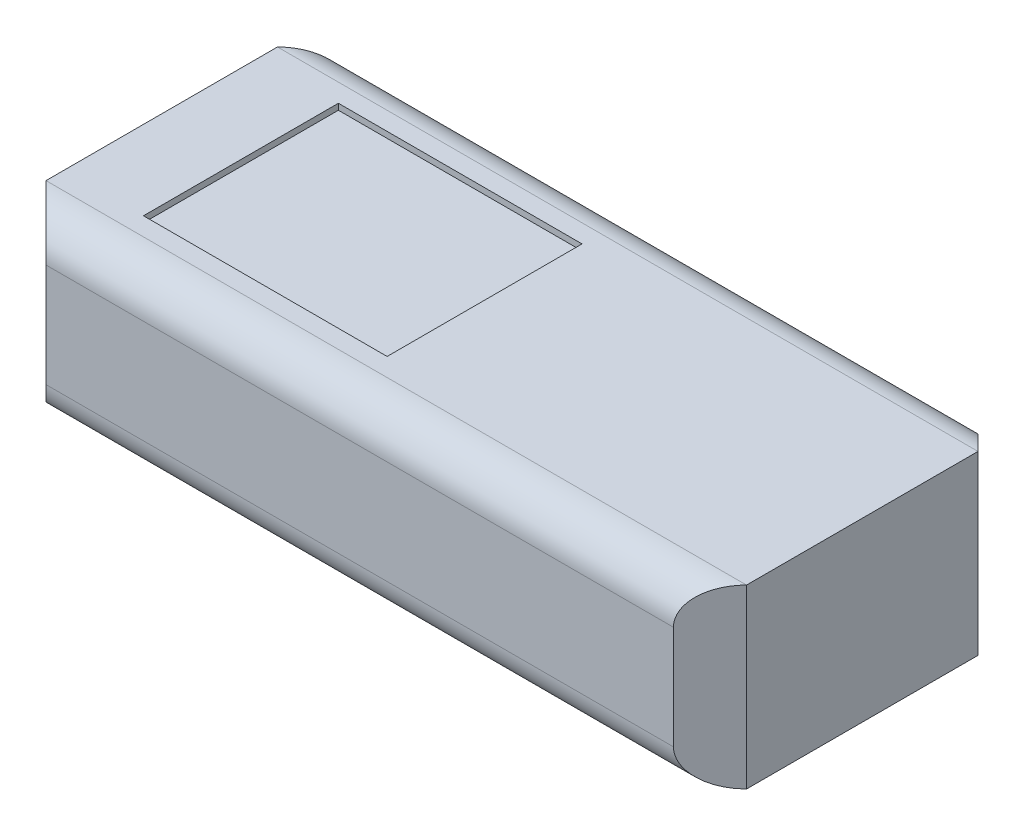
SolidWorks part; units mm, degrees
ref_plane "Front Plane" through (0, 0, 0) normal (0, 0, 1) x (1, 0, 0)
ref_plane "Top Plane" through (0, 0, 0) normal (0, 1, 0) x (1, 0, 0)
ref_plane "Right Plane" through (0, 0, 0) normal (1, 0, 0) x (0, 0, -1)
sketch "Sketch1" plane through (0, 0, 0) normal (0, 1, 0) x (1, 0, 0)
  line L0 (0, -55) -> (0, 55) construction
  line L1 (-57.5, 25) -> (57.5, 25)
  line L2 (-57.5, 25) -> (-57.5, -25)
  line L3 (-57.5, -25) -> (57.5, -25)
  line L4 (57.5, 25) -> (57.5, -25)
  line L5 (-55, 0) -> (55, 0) construction
  dimension "D1" = 50
  dimension "D2" = 115
  dimension "D3" = 57.5
  dimension "D4" = 25
extrude "Boss-Extrude1" add sketch "Sketch1" along normal blind 29
chamfer "Chamfer1" distance 6 angle 45 4 edges at (57.5, 14.5, -25) (57.5, 14.5, 25) (-57.5, 14.5, -25) (-57.5, 14.5, 25)
fillet "Fillet1" radius 6 4 edges at (0, 0, 25) (0, 0, -25) (0, 29, -25) (0, 29, 25)
sketch "Sketch2" plane through (0, 29, 0) normal (0, 1, 0) x (1, 0, 0)
  line L0 (-15.95, 0) -> (15.95, 0) construction
  line L1 (-44.5, 16) -> (-4.5, 16)
  line L2 (-44.5, 16) -> (-44.5, -16)
  line L3 (-44.5, -16) -> (-4.5, -16)
  line L4 (-4.5, 16) -> (-4.5, -16)
  line L5 (-57.5, 19) -> (-57.5, -19) construction
  dimension "D1" = 40
  dimension "D2" = 32
  dimension "D3" = 16
  dimension "D4" = 13
extrude "Cut-Extrude1" cut sketch "Sketch2" against normal blind 1
sketch "Sketch3" plane through (-57.5, 0, 0) normal (-1, 0, 0) x (0, 0, 1)
  line L0 (-8.7502, 13.3262) -> (-4.3677, 12.1169)
  line L1 (-7.0465, 18.9319) -> (-2.5893, 17.5208)
  arc A0 (-4.3677, 12.1169) -> (-2.5893, 17.5208) centre (4.6323, 12.1497) ccw
  arc A1 (-7.0465, 18.9319) -> (-8.7502, 13.3262) centre (-7.9707, 16.1511) ccw
  dimension "D1" = 18
extrude "Cut-Extrude2" cut sketch "Sketch3" against normal blind 4
sketch "Sketch4" plane through (-53.5, 0, 0) normal (-1, 0, 0) x (0, 0, 1)
  circle A0 centre (-2.1168, 14.0695) radius 2.0313
extrude "Cut-Extrude3" cut sketch "Sketch4" against normal blind 4
